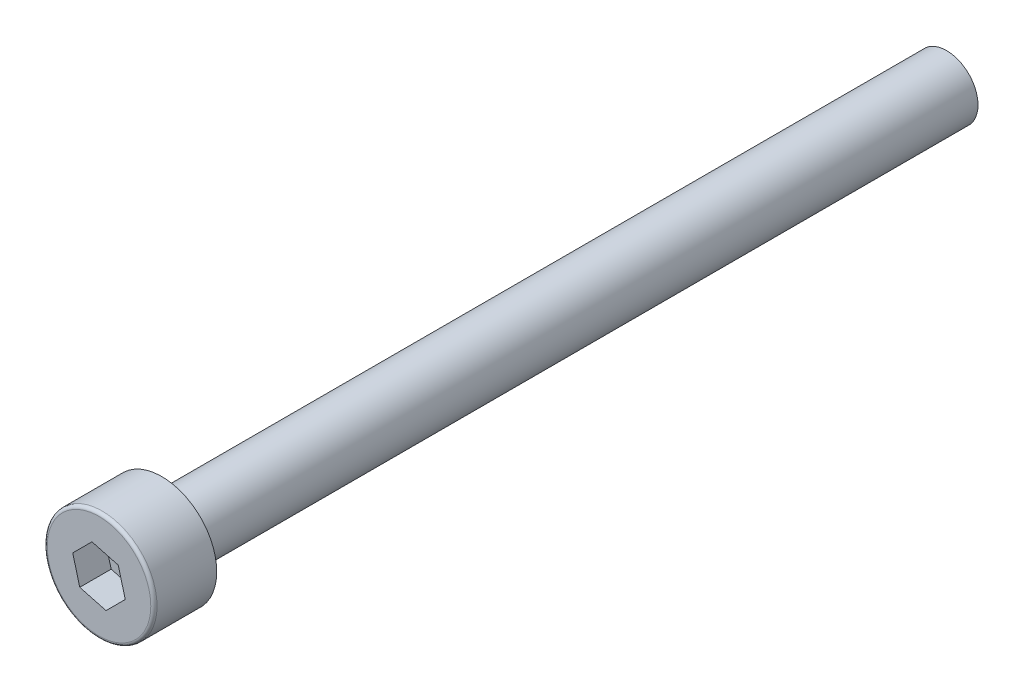
SolidWorks part; units mm, degrees
ref_plane "前视基准面" through (0, 0, 0) normal (0, 0, 1) x (1, 0, 0)
ref_plane "上视基准面" through (0, 0, 0) normal (0, 1, 0) x (1, 0, 0)
ref_plane "右视基准面" through (0, 0, 0) normal (1, 0, 0) x (0, 0, -1)
sketch "草图1" plane through (0, 0, 0) normal (0, 0, 1) x (1, 0, 0)
  circle A0 centre (0, 0) radius 3.5
  dimension "D1" = 7
extrude "凸台-拉伸1" add sketch "草图1" along normal blind 4
sketch "草图2" plane through (0, 0, 4) normal (0, 0, 1) x (1, 0, 0)
  line L1 (-1.2247, -1.2247) -> (0.4483, -1.673)
  line L2 (0.4483, -1.673) -> (1.673, -0.4483)
  line L3 (1.673, -0.4483) -> (1.2247, 1.2247)
  line L4 (1.2247, 1.2247) -> (-0.4483, 1.673)
  line L5 (-0.4483, 1.673) -> (-1.673, 0.4483)
  line L6 (-1.673, 0.4483) -> (-1.2247, -1.2247)
  circle A0 centre (0, 0) radius 1.5 construction
  dimension "D1" = 3
extrude "切除-拉伸1" cut sketch "草图2" against normal blind 2
sketch "草图3" plane through (0, 0, 0) normal (0, 0, -1) x (-1, 0, 0)
  circle A0 centre (0, 0) radius 2
  dimension "D1" = 4
extrude "凸台-拉伸2" add sketch "草图3" along normal blind 50
fillet "圆角1" radius 0.2 1 edges at (3.5, 0, 4)
